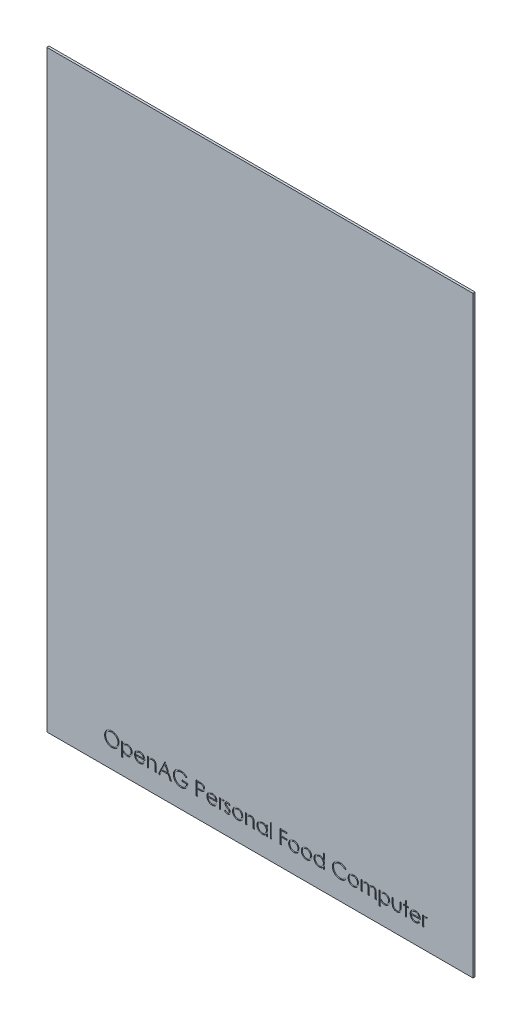
SolidWorks part; units mm, degrees
material "Acrylic (Medium-high impact)"
ref_plane "Front Plane" through (0, 0, 0) normal (0, 0, 1) x (1, 0, 0)
ref_plane "Top Plane" through (0, 0, 0) normal (0, 1, 0) x (1, 0, 0)
ref_plane "Right Plane" through (0, 0, 0) normal (1, 0, 0) x (0, 0, -1)
sketch "Sketch1" plane through (0, 0, 0) normal (0, 0, 1) x (1, 0, 0)
  line L1 (292.1, -406.4) -> (-292.1, -406.4)
  line L2 (292.1, -406.4) -> (292.1, 406.4)
  line L3 (292.1, 406.4) -> (-292.1, 406.4)
  line L4 (-292.1, -406.4) -> (-292.1, 406.4)
  line L5 (292.1, -406.4) -> (-292.1, 406.4) construction
  line L6 (292.1, 406.4) -> (-292.1, -406.4) construction
  point P0 (0, 0)
  dimension "D1" = 584.2
  dimension "D2" = 812.8
extrude "Boss-Extrude1" add sketch "Sketch1" along normal blind 3.0734
sketch "Sketch2" plane through (0, 0, 3.0734) normal (0, 0, 1) x (1, 0, 0)
  text T0 "OpenAG Personal Food Computer" font "Century Gothic" height in points 72
extrude "Text" cut sketch "Sketch2" against normal blind 1.27
equation "\"Height\"= 32in"
equation "\"Width\"= 23in"
equation "\"Depth\"= 20in"
equation "\"Plexi\"= .121in"
equation "\"MagnetThickness\"=3mm"
equation "\"MagnetDiameter\"=12mm"
equation "\"DoorPlexi\" = \"Plexi\""
equation "\"BasePlateThickness\" = 0.5in"
equation "\"BasePlateWidth\" = \"Width\"+\"EBWidth\"-2*\"Plexi\""
equation "\"BasePlateDepth\" = \"Depth\"-\"Plexi\"-\"DoorPlexi\""
equation "\"Boxsize\" = .75in"
equation "\"Boxinner\" = .625in"
equation "\"CornerCube\" = 0.75in"
equation "\"FingerLength\" = 1.125in"
equation "\"FingerWidth\" = .625in"
equation "\"Cutwidth\"= .016in"
equation "\"Earsize\"= 1in + \"Cutwidth\" /2"
equation "\"Slotsize\" = 1in - \"CutWidth\" / 2"
equation "\"InnerWidth\" = \"Width\" - 2* \"Plexi\""
equation "\"InnerHeight\" = \"Height\" -2 * \"Plexi\""
equation "\"InnerDepth\" = \"Depth\" - 2*\"Plexi\""
equation "\"RearNumHoles\" = 7"
equation "\"RearHolesBorder\" = 2.2"
equation "\"RearHoleSpacing\" = (\"Width\" - 2*\"RearHolesBorder\") / (\"RearNumHoles\"-1)"
equation "\"RearBarLength\" = (\"InnerWidth\"-2*\"CornerCube\")"
equation "\"RearTopNumHoles\" = 6"
equation "\"RearTopHolesBorder\" = 2.5"
equation "\"RearTopHolesSpacing\" = (\"Width\" - 2*\"RearTopHolesBorder\") / (\"RearTopNumHoles\"-1)"
equation "\"SideTopNumHoles\" = 5"
equation "\"SideTopHoleOffset\"=\"CornerCube\"+\"FingerLength\"+\"Plexi\"+.5"
equation "\"SideTopHoleSpacing\" = (\"TopBarDepth\"-2*\"SideTopHoleOffset\") / (\"SideTopNumHoles\"-1)"
equation "\"SideHorizNumHoles\" = 6"
equation "\"SideHorizHoleBorder\" = 2.25"
equation "\"SideHorizHoleSpacing\" = (\"TopBarDepth\"-2*\"SideHorizHoleBorder\") / (\"SideHorizNumHoles\"-1)"
equation "\"SideVertBarLength\"=\"Height\"-\"BasePlateThickness\"-2*\"CornerCube\"-\"Plexi\""
equation "\"SideVertNumHoles\" = 6"
equation "\"SideVertHolesBorder\" = \"CornerCube\"+\"FingerLength\"+.9"
equation "\"SideVertHoleSpacing\" = (\"InnerHeight\" - 2*\"SideVertHolesBorder\") / (\"SideVertNumHoles\"-1)"
equation "\"RearSideVertNumHoles\" = 7"
equation "\"RearSideVertHolesBorder\" = 2.5"
equation "\"RearSideVertHoleSpacing\" = (\"InnerHeight\" - 2*\"RearSideVertHolesBorder\") / (\"RearSideVertNumHoles\"-1)"
equation "\"RivetDia\" = .228in"
equation "\"SlotDepth\" = \"Plexi\" + 0.75in + .005in"
equation "\"SideSlotWidth\"   = \"Plexi\"+.005in"
equation "\"SidePanelVertSpacing\" = (\"Height\"-2*(1.75-\"Plexi\")) / 5"
equation "\"BottomPanelSideHoleSpacing\" = (\"InnerDepth\"-2*(1.75-\"Plexi\")) / 4"
equation "\"FrontDoorGap\" = .1in"
equation "\"TopDepth\" = \"Depth\"-\"DoorPlexi\"-\"FrontDoorGap\""
equation "\"TopBarDepth\" = \"Depth\"-\"DoorPlexi\"-\"Plexi\"-2*\"MagnetThickness\"-2*\"CornerCube\""
equation "\"D1@Sketch1\"=\"Width\""
equation "\"D2@Sketch1\"=\"Height\""
equation "\"D1@Boss-Extrude1\"=\"DoorPlexi\""
